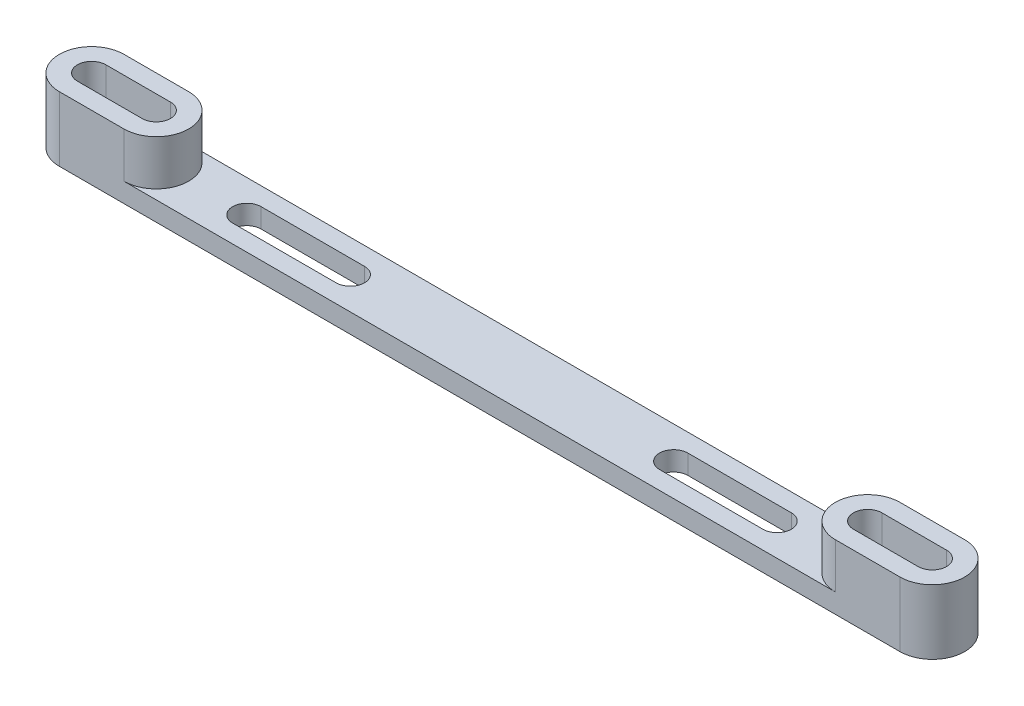
SolidWorks part; units mm, degrees
ref_plane "前视基准面" through (0, 0, 0) normal (0, 0, 1) x (1, 0, 0)
ref_plane "上视基准面" through (0, 0, 0) normal (0, 1, 0) x (1, 0, 0)
ref_plane "右视基准面" through (0, 0, 0) normal (1, 0, 0) x (0, 0, -1)
sketch "草图1" plane through (0, 0, 0) normal (0, 1, 0) x (1, 0, 0)
  line L0 (-65, 0) -> (65, 0) construction
  line L1 (-65, 5) -> (65, 5)
  line L2 (-65, -5) -> (65, -5)
  arc A0 (-65, 5) -> (-65, -5) centre (-65, 0) ccw
  arc A1 (65, -5) -> (65, 5) centre (65, 0) ccw
  point P3 (0, 0)
  point P8 (-70, 0)
  point P9 (70, 0)
  dimension "D2" = 5
  dimension "D1" = 140
extrude "凸台-拉伸1" add sketch "草图1" along normal blind 3
sketch "草图2" plane through (0, 3, 0) normal (0, 1, 0) x (1, 0, 0)
  line L0 (-65, 0) -> (-55, 0) construction
  line L1 (-65, 5) -> (-55, 5)
  line L2 (-65, -5) -> (-55, -5)
  line L3 (65, 5) -> (-65, 5) construction
  line L4 (0, 11.7911) -> (0, -10.8622) construction
  line L5 (65, 0) -> (55, 0) construction
  line L6 (65, 5) -> (55, 5)
  line L7 (65, -5) -> (55, -5)
  arc A0 (-65, 5) -> (-65, -5) centre (-65, 0) ccw
  arc A1 (-55, -5) -> (-55, 5) centre (-55, 0) ccw
  arc A2 (65, 5) -> (65, -5) centre (65, 0) cw
  arc A3 (55, -5) -> (55, 5) centre (55, 0) cw
  point P4 (-60, 0)
  point P15 (60, 0)
  dimension "D1" = 10
extrude "凸台-拉伸2" add sketch "草图2" along normal blind 7
sketch "草图3" plane through (0, 10, 0) normal (0, 1, 0) x (1, 0, 0)
  line L0 (-65, 0) -> (-55, 0) construction
  line L1 (-65, 0) -> (65, 0) construction
  line L2 (-65, 2.2) -> (-55, 2.2)
  line L3 (-65, -2.2) -> (-55, -2.2)
  line L4 (0, 5) -> (0, -5) construction
  line L5 (-65, 5) -> (65, 5) construction
  line L6 (-65, -5) -> (65, -5) construction
  line L7 (65, 0) -> (55, 0) construction
  line L8 (65, 2.2) -> (55, 2.2)
  line L9 (65, -2.2) -> (55, -2.2)
  arc A0 (-65, 2.2) -> (-65, -2.2) centre (-65, 0) ccw
  arc A1 (-55, -2.2) -> (-55, 2.2) centre (-55, 0) ccw
  arc A2 (65, 2.2) -> (65, -2.2) centre (65, 0) cw
  arc A3 (55, -2.2) -> (55, 2.2) centre (55, 0) cw
  point P5 (-60, 0)
  point P10 (-55, 5)
  point P20 (60, 0)
  point P25 (55, 5)
  dimension "D1" = 2.2
extrude "切除-拉伸1" cut sketch "草图3" against normal through all
sketch "草图4" plane through (0, 3, 0) normal (0, 1, 0) x (1, 0, 0)
  line L0 (-41, 0) -> (-25, 0) construction
  line L1 (-65, 0) -> (65, 0) construction
  line L2 (-41, 2.2) -> (-25, 2.2)
  line L3 (-41, -2.2) -> (-25, -2.2)
  line L4 (0, 5) -> (0, -5) construction
  line L5 (-65, 5) -> (65, 5) construction
  line L6 (-65, -5) -> (65, -5) construction
  line L7 (41, 0) -> (25, 0) construction
  line L8 (41, 2.2) -> (25, 2.2)
  line L9 (41, -2.2) -> (25, -2.2)
  arc A0 (-41, 2.2) -> (-41, -2.2) centre (-41, 0) ccw
  arc A1 (-25, -2.2) -> (-25, 2.2) centre (-25, 0) ccw
  arc A2 (41, 2.2) -> (41, -2.2) centre (41, 0) cw
  arc A3 (25, -2.2) -> (25, 2.2) centre (25, 0) cw
  point P4 (-33, 0)
  point P18 (33, 0)
  dimension "D1" = 2.2
  dimension "D2" = 29
  dimension "D3" = 16
extrude "切除-拉伸2" cut sketch "草图4" against normal through all
